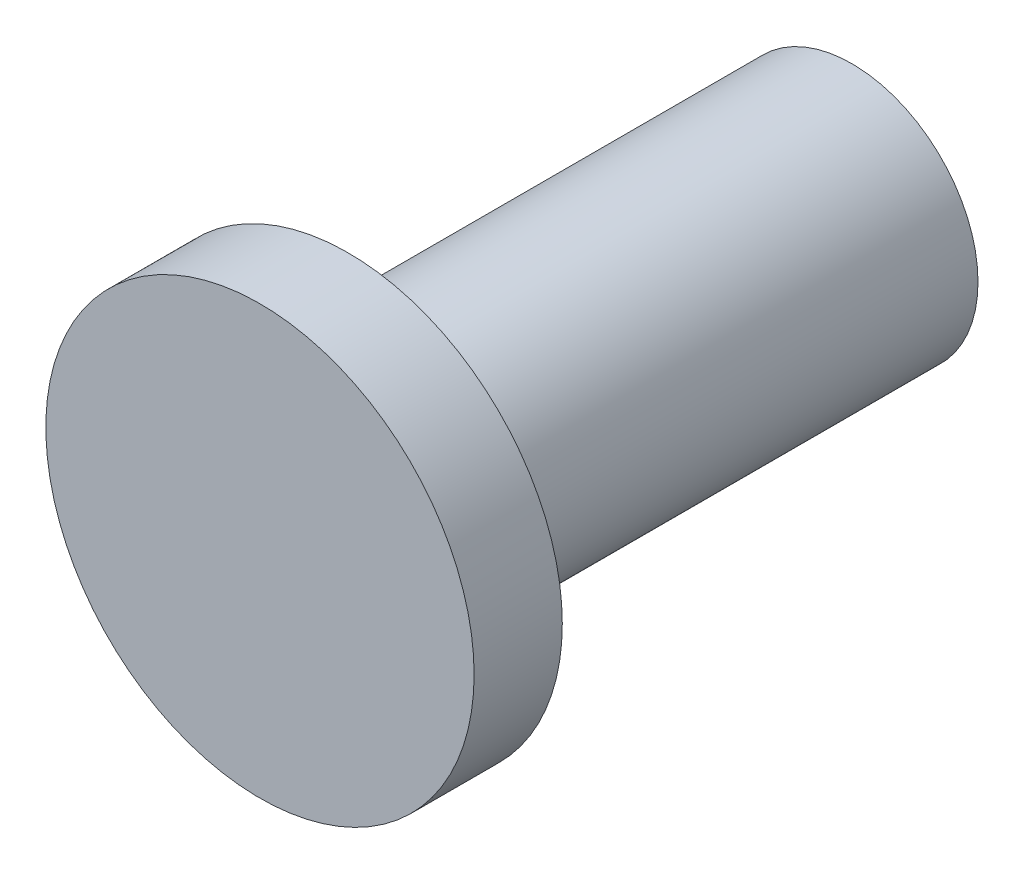
SolidWorks part; units mm, degrees
material "AISI 4340 Steel, normalized"
ref_plane "Front Plane" through (0, 0, 0) normal (0, 0, 1) x (1, 0, 0)
ref_plane "Top Plane" through (0, 0, 0) normal (0, 1, 0) x (1, 0, 0)
ref_plane "Right Plane" through (0, 0, 0) normal (1, 0, 0) x (0, 0, -1)
sketch "Sketch1" plane through (0, 0, 0) normal (0, 0, 1) x (1, 0, 0)
  circle A0 centre (0, 0) radius 1
extrude "Thread_Envelope" add sketch "Sketch1" along normal blind 4 from offset 4
sketch "Sketch2" plane through (0, 0, 0) normal (0, 0, 1) x (1, 0, 0)
  circle A0 centre (0, 0) radius 1.7
extrude "Head_Envelope" add sketch "Sketch2" along normal blind 0.7
